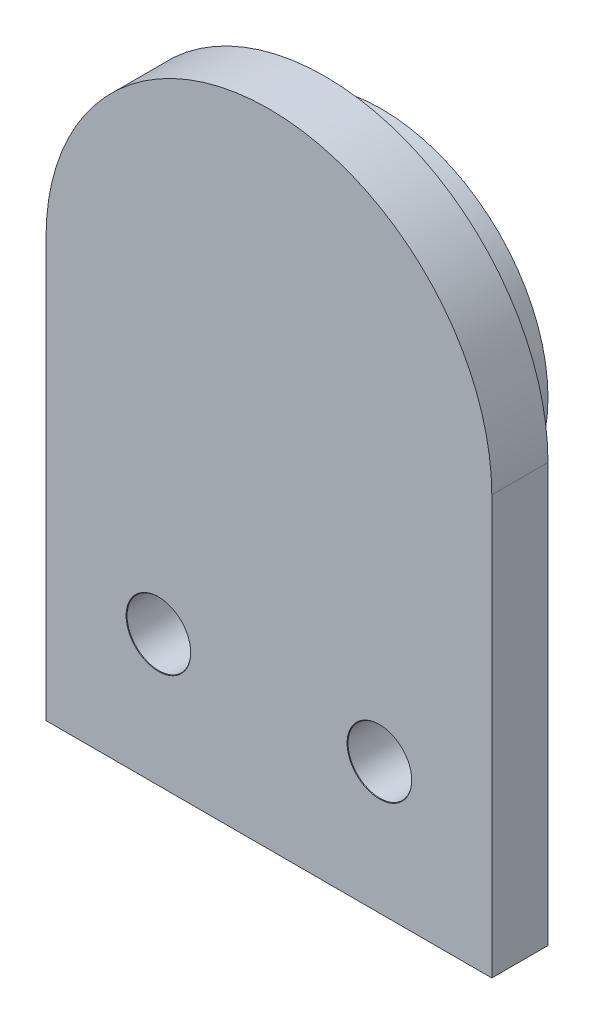
SolidWorks part; units mm, degrees
ref_plane "Front Plane" through (0, 0, 0) normal (0, 0, 1) x (1, 0, 0)
ref_plane "Top Plane" through (0, 0, 0) normal (0, 1, 0) x (1, 0, 0)
ref_plane "Right Plane" through (0, 0, 0) normal (1, 0, 0) x (0, 0, -1)
sketch "Sketch1" plane through (0, 0, 0) normal (0, 0, 1) x (1, 0, 0)
  line L0 (-11.9, 0) -> (-11.9, -22.34)
  line L1 (-11.9, -22.34) -> (11.9, -22.34)
  line L2 (11.9, -22.34) -> (11.9, 0)
  arc A0 (11.9, 0) -> (-11.9, 0) centre (0, 0) ccw
  dimension "D1" = 22.34
  dimension "D2" = 23.8
extrude "Boss-Extrude1" add sketch "Sketch1" along normal blind 3
sketch "Sketch2" plane through (0, 0, 0) normal (0, 0, -1) x (-1, 0, 0)
  circle A0 centre (0, 0) radius 8.9
  dimension "D1" = 17.8
extrude "Boss-Extrude2" add sketch "Sketch2" along normal blind 3
sketch "Sketch3" plane through (0, 0, -3) normal (0, 0, -1) x (-1, 0, 0)
  circle A0 centre (0, 0) radius 2
  dimension "D1" = 4
extrude "Boss-Extrude3" add sketch "Sketch3" along normal blind 3
hole_wizard "M3 Clearance Hole1" positions "3DSketch1" profile "Sketch5" hole size "M3" standard "ANSI Metric" end condition through all
sketch3d "3DSketch1"
  line L0 (-11.9, -22.34, 3) -> (11.9, -22.34, 3) construction
  line L1 (-11.9, 0, 3) -> (-11.9, -22.34, 3) construction
  line L2 (11.9, -22.34, 3) -> (11.9, 0, 3) construction
  point P0 (-5.9, -15.34, 3)
  point P2 (5.9, -15.34, 3)
  dimension "D1" = 7
  dimension "D2" = 6
  dimension "D3" = 6
sketch "Sketch5" plane through (-5.9, -15.34, 3) normal (1, 0, 0) x (0, -1, 0)
  line L0 (0, 0) -> (0, 9)
  line L1 (0, 9) -> (1.7, 9)
  line L2 (1.7, 9) -> (1.7, 0.025)
  line L3 (1.7, 0.025) -> (1.725, 0)
  line L5 (1.725, 0) -> (0, 0)
  line L6 (-1.7, 0.025) -> (-1.725, 0) construction
  line L11 (0, -6.35) -> (0, 107.95) construction
  dimension "Thru Hole Dia." = 3.4
  dimension "Thru Hole Depth" = 9
  dimension "Near C'Sink Dia." = 3.45
  dimension "Near C'Sink Angle" = 90
